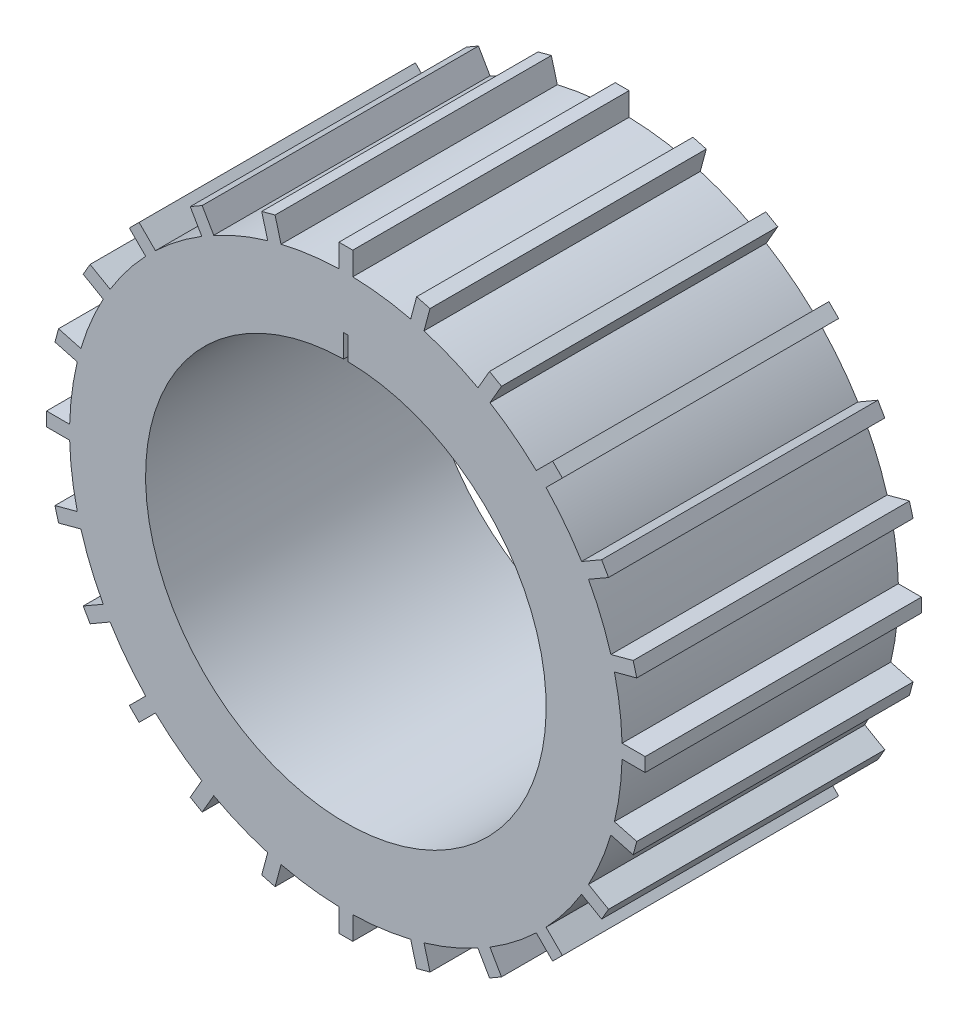
SolidWorks part; units mm, degrees
ref_plane "Front Plane" through (0, 0, 0) normal (0, 0, 1) x (1, 0, 0)
ref_plane "Top Plane" through (0, 0, 0) normal (0, 1, 0) x (1, 0, 0)
ref_plane "Right Plane" through (0, 0, 0) normal (1, 0, 0) x (0, 0, -1)
ref_plane "Plane1"
sketch "Sketch1" plane through (0, 0, 0) normal (0, 0, 1) x (1, 0, 0)
  circle A0 centre (0, 0) radius 60
  circle A1 centre (0, 0) radius 43.5
  dimension "D1" = 87
  dimension "D2" = 120
extrude "Extrusion1" add sketch "Sketch1" along normal blind 60 contours A0 A1
ref_plane "Plane2"
ref_plane "Plane3"
sketch "Sketch3" plane through (0, 0, 60) normal (0, 0, 1) x (1, 0, 0)
  line L0 (-0.5, 48.5) -> (-0.5, 43.4971)
  line L1 (0.5, 43.4971) -> (0.5, 48.5)
  line L2 (0.5, 48.5) -> (-0.5, 48.5)
  arc A0 (0.5, 43.4971) -> (-0.5, 43.4971) centre (0, 0) ccw
extrude "Extrusion3" cut sketch "Sketch3" against normal blind 60
sketch "Sketch4" plane through (0, 0, 60) normal (0, 0, 1) x (1, 0, 0)
  line L0 (14.0754, 58.3257) -> (15.3743, 63.1734)
  line L1 (1.5, 59.9812) -> (1.5, 65)
  line L2 (-1.5, 59.9812) -> (-1.5, 65)
  line L3 (15.3743, 63.1734) -> (18.2721, 62.397)
  line L4 (16.9732, 57.5492) -> (18.2721, 62.397)
  line L5 (-1.5, 65) -> (1.5, 65)
  line L6 (28.6916, 52.6953) -> (31.201, 57.0417)
  line L7 (31.201, 57.0417) -> (33.799, 55.5417)
  line L8 (31.2897, 51.1953) -> (33.799, 55.5417)
  line L9 (41.3525, 43.4738) -> (44.9013, 47.0226)
  line L10 (44.9013, 47.0226) -> (47.0226, 44.9013)
  line L11 (43.4738, 41.3525) -> (47.0226, 44.9013)
  line L12 (51.1953, 31.2897) -> (55.5417, 33.799)
  line L13 (55.5417, 33.799) -> (57.0417, 31.201)
  line L14 (52.6953, 28.6916) -> (57.0417, 31.201)
  line L15 (57.5492, 16.9732) -> (62.397, 18.2721)
  line L16 (62.397, 18.2721) -> (63.1734, 15.3743)
  line L17 (58.3257, 14.0754) -> (63.1734, 15.3743)
  line L18 (59.9812, 1.5) -> (65, 1.5)
  line L19 (65, 1.5) -> (65, -1.5)
  line L20 (59.9812, -1.5) -> (65, -1.5)
  line L21 (58.3257, -14.0754) -> (63.1734, -15.3743)
  line L22 (63.1734, -15.3743) -> (62.397, -18.2721)
  line L23 (57.5492, -16.9732) -> (62.397, -18.2721)
  line L24 (52.6953, -28.6916) -> (57.0417, -31.201)
  line L25 (57.0417, -31.201) -> (55.5417, -33.799)
  line L26 (51.1953, -31.2897) -> (55.5417, -33.799)
  line L27 (43.4738, -41.3525) -> (47.0226, -44.9013)
  line L28 (47.0226, -44.9013) -> (44.9013, -47.0226)
  line L29 (41.3525, -43.4738) -> (44.9013, -47.0226)
  line L30 (31.2897, -51.1953) -> (33.799, -55.5417)
  line L31 (33.799, -55.5417) -> (31.201, -57.0417)
  line L32 (28.6916, -52.6953) -> (31.201, -57.0417)
  line L33 (16.9732, -57.5492) -> (18.2721, -62.397)
  line L34 (18.2721, -62.397) -> (15.3743, -63.1734)
  line L35 (14.0754, -58.3257) -> (15.3743, -63.1734)
  line L36 (1.5, -59.9812) -> (1.5, -65)
  line L37 (1.5, -65) -> (-1.5, -65)
  line L38 (-1.5, -59.9812) -> (-1.5, -65)
  line L39 (-14.0754, -58.3257) -> (-15.3743, -63.1734)
  line L40 (-15.3743, -63.1734) -> (-18.2721, -62.397)
  line L41 (-16.9732, -57.5492) -> (-18.2721, -62.397)
  line L42 (-28.6916, -52.6953) -> (-31.201, -57.0417)
  line L43 (-31.201, -57.0417) -> (-33.799, -55.5417)
  line L44 (-31.2897, -51.1953) -> (-33.799, -55.5417)
  line L45 (-41.3525, -43.4738) -> (-44.9013, -47.0226)
  line L46 (-44.9013, -47.0226) -> (-47.0226, -44.9013)
  line L47 (-43.4738, -41.3525) -> (-47.0226, -44.9013)
  line L48 (-51.1953, -31.2897) -> (-55.5417, -33.799)
  line L49 (-55.5417, -33.799) -> (-57.0417, -31.201)
  line L50 (-52.6953, -28.6916) -> (-57.0417, -31.201)
  line L51 (-57.5492, -16.9732) -> (-62.397, -18.2721)
  line L52 (-62.397, -18.2721) -> (-63.1734, -15.3743)
  line L53 (-58.3257, -14.0754) -> (-63.1734, -15.3743)
  line L54 (-59.9812, -1.5) -> (-65, -1.5)
  line L55 (-65, -1.5) -> (-65, 1.5)
  line L56 (-59.9812, 1.5) -> (-65, 1.5)
  line L57 (-58.3257, 14.0754) -> (-63.1734, 15.3743)
  line L58 (-63.1734, 15.3743) -> (-62.397, 18.2721)
  line L59 (-57.5492, 16.9732) -> (-62.397, 18.2721)
  line L60 (-52.6953, 28.6916) -> (-57.0417, 31.201)
  line L61 (-57.0417, 31.201) -> (-55.5417, 33.799)
  line L62 (-51.1953, 31.2897) -> (-55.5417, 33.799)
  line L63 (-43.4738, 41.3525) -> (-47.0226, 44.9013)
  line L64 (-47.0226, 44.9013) -> (-44.9013, 47.0226)
  line L65 (-41.3525, 43.4738) -> (-44.9013, 47.0226)
  line L66 (-31.2897, 51.1953) -> (-33.799, 55.5417)
  line L67 (-33.799, 55.5417) -> (-31.201, 57.0417)
  line L68 (-28.6916, 52.6953) -> (-31.201, 57.0417)
  line L69 (-16.9732, 57.5492) -> (-18.2721, 62.397)
  line L70 (-18.2721, 62.397) -> (-15.3743, 63.1734)
  line L71 (-14.0754, 58.3257) -> (-15.3743, 63.1734)
  arc A0 (16.9732, 57.5492) -> (14.0754, 58.3257) centre (0, 0) ccw
  arc A1 (1.5, 59.9812) -> (-1.5, 59.9812) centre (0, 0) ccw
  arc A2 (31.2897, 51.1953) -> (28.6916, 52.6953) centre (0, 0) ccw
  arc A3 (43.4738, 41.3525) -> (41.3525, 43.4738) centre (0, 0) ccw
  arc A4 (52.6953, 28.6916) -> (51.1953, 31.2897) centre (0, 0) ccw
  arc A5 (58.3257, 14.0754) -> (57.5492, 16.9732) centre (0, 0) ccw
  arc A6 (59.9812, -1.5) -> (59.9812, 1.5) centre (0, 0) ccw
  arc A7 (57.5492, -16.9732) -> (58.3257, -14.0754) centre (0, 0) ccw
  arc A8 (51.1953, -31.2897) -> (52.6953, -28.6916) centre (0, 0) ccw
  arc A9 (41.3525, -43.4738) -> (43.4738, -41.3525) centre (0, 0) ccw
  arc A10 (28.6916, -52.6953) -> (31.2897, -51.1953) centre (0, 0) ccw
  arc A11 (14.0754, -58.3257) -> (16.9732, -57.5492) centre (0, 0) ccw
  arc A12 (-1.5, -59.9812) -> (1.5, -59.9812) centre (0, 0) ccw
  arc A13 (-16.9732, -57.5492) -> (-14.0754, -58.3257) centre (0, 0) ccw
  arc A14 (-31.2897, -51.1953) -> (-28.6916, -52.6953) centre (0, 0) ccw
  arc A15 (-43.4738, -41.3525) -> (-41.3525, -43.4738) centre (0, 0) ccw
  arc A16 (-52.6953, -28.6916) -> (-51.1953, -31.2897) centre (0, 0) ccw
  arc A17 (-58.3257, -14.0754) -> (-57.5492, -16.9732) centre (0, 0) ccw
  arc A18 (-59.9812, 1.5) -> (-59.9812, -1.5) centre (0, 0) ccw
  arc A19 (-57.5492, 16.9732) -> (-58.3257, 14.0754) centre (0, 0) ccw
  arc A20 (-51.1953, 31.2897) -> (-52.6953, 28.6916) centre (0, 0) ccw
  arc A21 (-41.3525, 43.4738) -> (-43.4738, 41.3525) centre (0, 0) ccw
  arc A22 (-28.6916, 52.6953) -> (-31.2897, 51.1953) centre (0, 0) ccw
  arc A23 (-14.0754, 58.3257) -> (-16.9732, 57.5492) centre (0, 0) ccw
  point P101 (0, 0)
  dimension "D1" = 24
extrude "Boss-Extrude1" add sketch "Sketch4" against normal blind 60
